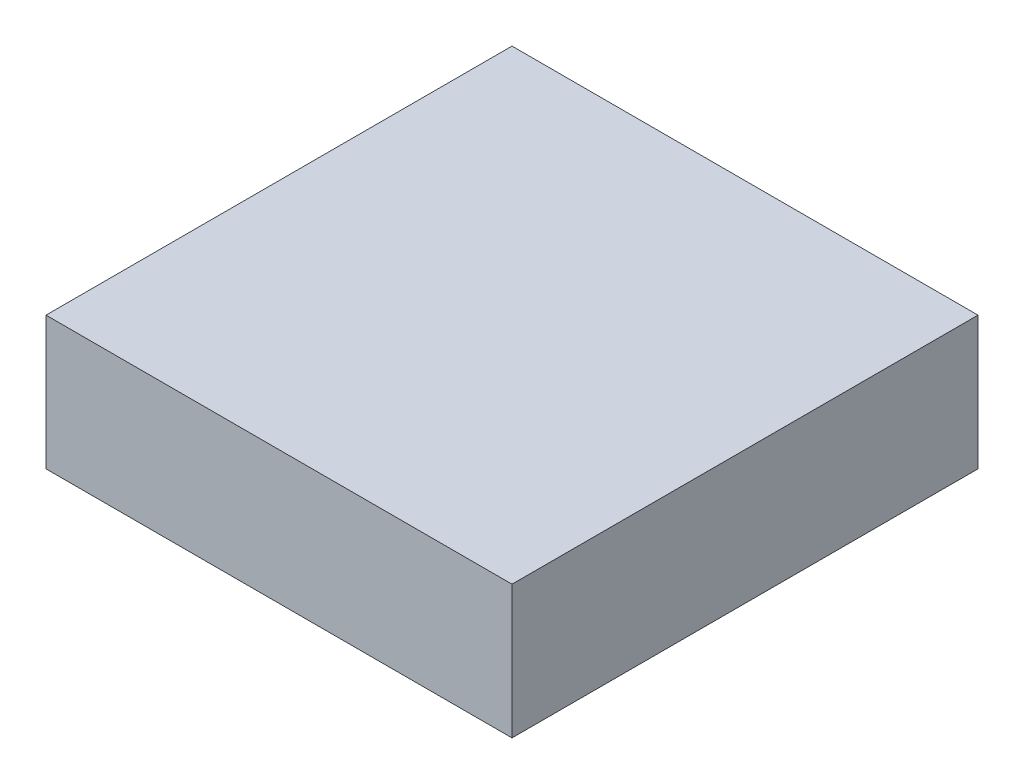
SolidWorks part; units mm, degrees
ref_plane "Front Plane" through (0, 0, 0) normal (0, 0, 1) x (1, 0, 0)
ref_plane "Top Plane" through (0, 0, 0) normal (0, 1, 0) x (1, 0, 0)
ref_plane "Right Plane" through (0, 0, 0) normal (1, 0, 0) x (0, 0, -1)
sketch "Sketch1" plane through (0, 0, 0) normal (0, 1, 0) x (1, 0, 0)
  line L1 (-17.5, 17.5) -> (17.5, 17.5)
  line L2 (-17.5, 17.5) -> (-17.5, -17.5)
  line L3 (-17.5, -17.5) -> (17.5, -17.5)
  line L4 (17.5, 17.5) -> (17.5, -17.5)
  line L5 (-17.5, 17.5) -> (17.5, -17.5) construction
  line L6 (-17.5, -17.5) -> (17.5, 17.5) construction
  point P0 (0, 0)
  dimension "D1" = 35
  dimension "D2" = 35
extrude "Boss-Extrude1" add sketch "Sketch1" along normal blind 10
